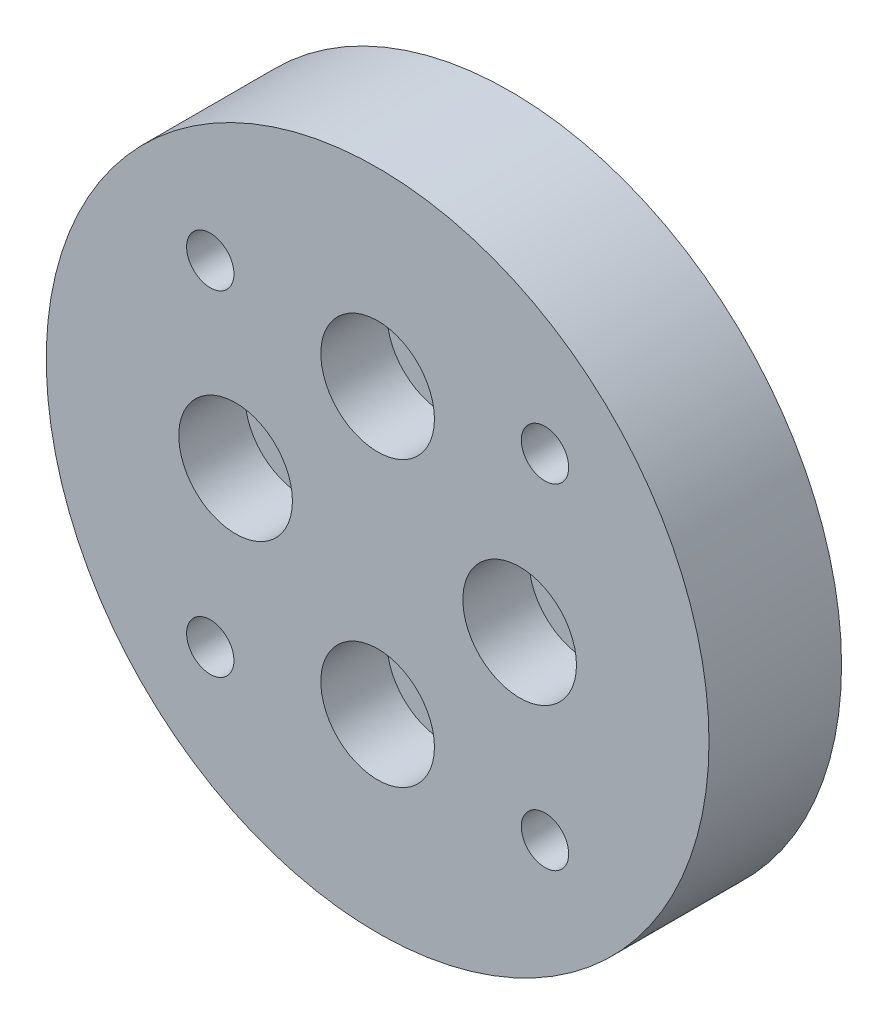
SolidWorks part; units mm, degrees
ref_plane "前视基准面" through (0, 0, 0) normal (0, 0, 1) x (1, 0, 0)
ref_plane "上视基准面" through (0, 0, 0) normal (0, 1, 0) x (1, 0, 0)
ref_plane "右视基准面" through (0, 0, 0) normal (1, 0, 0) x (0, 0, -1)
sketch "草图1" plane through (0, 0, 0) normal (0, 0, 1) x (1, 0, 0)
  line L0 (0, 0) -> (8.8388, 8.8388) construction
  line L1 (0, 0) -> (0, 12.5) construction
  circle A0 centre (0, 0) radius 17.5
  circle A1 centre (0, 0) radius 7.5 construction
  circle A2 centre (0, 7.5) radius 1.25
  circle A3 centre (7.5, 0) radius 1.25
  circle A4 centre (0, -7.5) radius 1.25
  circle A5 centre (-7.5, 0) radius 1.25
  circle A6 centre (0, 0) radius 12.5 construction
  circle A7 centre (8.8388, 8.8388) radius 1.25
  circle A8 centre (8.8388, -8.8388) radius 1.25
  circle A9 centre (-8.8388, -8.8388) radius 1.25
  circle A10 centre (-8.8388, 8.8388) radius 1.25
  point P15 (0, 0)
  point P17 (0, 0)
  point P18 (-8.5566, 7.7002)
  point P19 (0, 0)
  point P26 (0, 0)
  dimension "D1" = 35
  dimension "D2" = 15
  dimension "D3" = 4
  dimension "D4" = 2.5
  dimension "D5" = 25
  dimension "D7" = 4
  dimension "D8" = 2.5
  dimension "D6" = 45
extrude "凸台-拉伸1" add sketch "草图1" along normal blind 7
cosmetic thread "装饰螺纹线1" parameters "D1"=5, "D2"=3
cosmetic thread "装饰螺纹线2" parameters "D1"=5, "D2"=3
cosmetic thread "装饰螺纹线3" parameters "D1"=5, "D2"=3
cosmetic thread "装饰螺纹线4" parameters "D1"=5, "D2"=3
cosmetic thread "装饰螺纹线5" parameters "D1"=5, "D2"=3
cosmetic thread "装饰螺纹线6" parameters "D1"=5, "D2"=3
cosmetic thread "装饰螺纹线7" parameters "D1"=5, "D2"=3
cosmetic thread "装饰螺纹线8" parameters "D1"=5, "D2"=3
sketch "草图2" plane through (0, 0, 7) normal (0, 0, 1) x (1, 0, 0)
  circle A0 centre (0, 7.5) radius 3
  circle A1 centre (7.5, 0) radius 3
  circle A2 centre (0, -7.5) radius 3
  circle A3 centre (-7.5, 0) radius 3
  dimension "D1" = 6
extrude "切除-拉伸1" cut sketch "草图2" against normal blind 3.5
